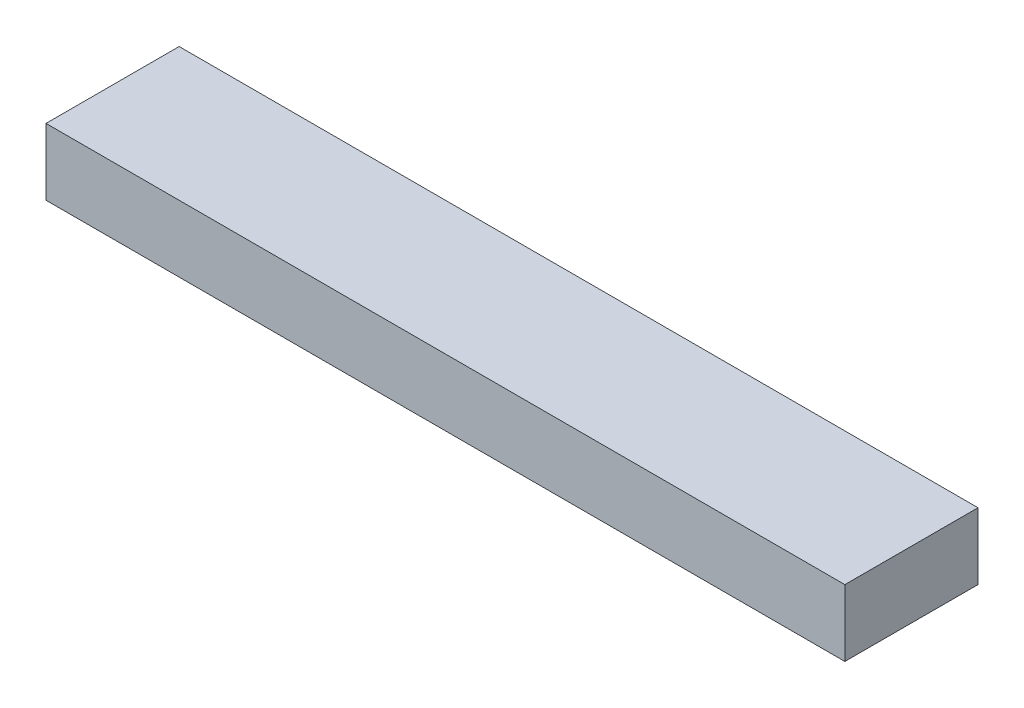
SolidWorks part; units mm, degrees
material "Acrylic (Medium-high impact)"
ref_plane "Front Plane" through (0, 0, 0) normal (0, 0, 1) x (1, 0, 0)
ref_plane "Top Plane" through (0, 0, 0) normal (0, 1, 0) x (1, 0, 0)
ref_plane "Right Plane" through (0, 0, 0) normal (1, 0, 0) x (0, 0, -1)
sketch "Sketch1" plane through (0, 0, 0) normal (0, 1, 0) x (1, 0, 0)
  line L1 (0, 0) -> (38.1, 0)
  line L2 (0, 0) -> (0, 6.35)
  line L3 (0, 6.35) -> (38.1, 6.35)
  line L4 (38.1, 0) -> (38.1, 6.35)
  dimension "D1" = 38.1
  dimension "D2" = 6.35
extrude "Boss-Extrude1" add sketch "Sketch1" along normal blind 3.175
